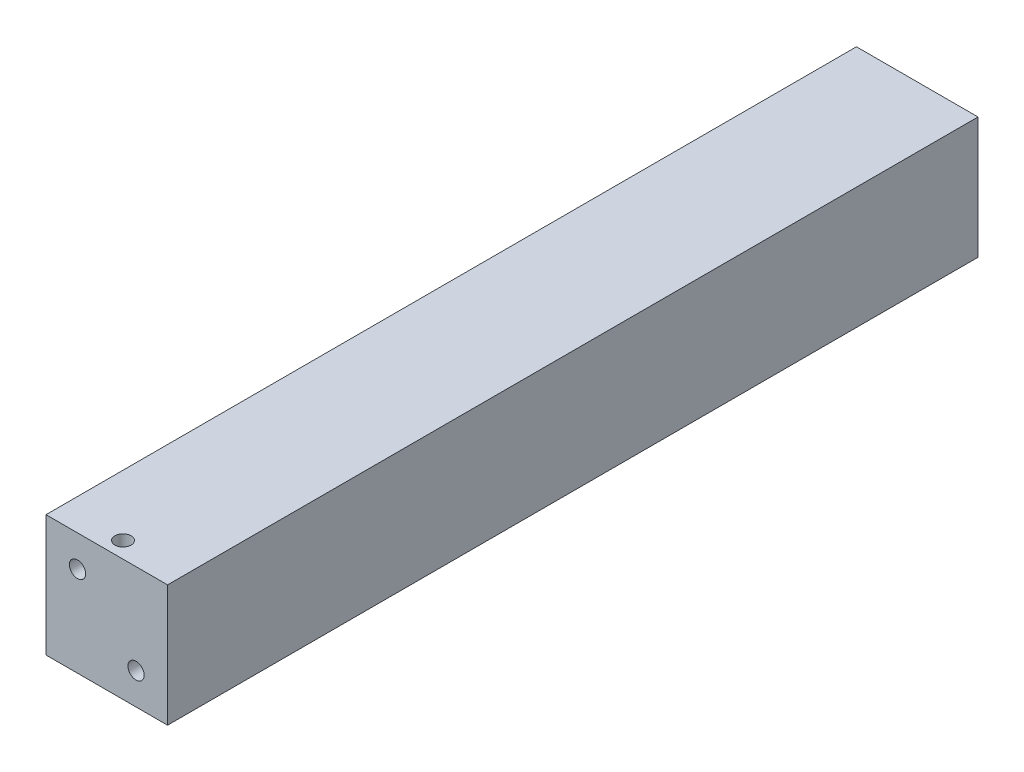
SolidWorks part; units mm, degrees
ref_plane "Alzado" through (0, 0, 0) normal (0, 0, 1) x (1, 0, 0)
ref_plane "Planta" through (0, 0, 0) normal (0, 1, 0) x (1, 0, 0)
ref_plane "Vista lateral" through (0, 0, 0) normal (1, 0, 0) x (0, 0, -1)
sketch "Croquis1" plane through (0, 0, 0) normal (0, 0, 1) x (1, 0, 0)
  line L1 (-15, -15) -> (15, -15)
  line L2 (-15, -15) -> (-15, 15)
  line L3 (-15, 15) -> (15, 15)
  line L4 (15, -15) -> (15, 15)
  line L5 (-15, -15) -> (15, 15) construction
  line L6 (-15, 15) -> (15, -15) construction
  point P0 (0, 0)
  dimension "D1" = 30
extrude "Saliente-Extruir1" add sketch "Croquis1" along normal blind 200
sketch "Croquis2" plane through (0, 0, 200) normal (0, 0, 1) x (1, 0, 0)
  line L0 (-15, 15) -> (15, -15) construction
  line L1 (-15, -15) -> (15, 15) construction
  circle A1 centre (-7.2218, 7.2218) radius 2
  circle A2 centre (7.2218, -7.2218) radius 2
  dimension "D1" = 11
extrude "Cortar-Extruir1" cut sketch "Croquis2" against normal blind 25
sketch "Croquis3" plane through (0, 15, 0) normal (0, 1, 0) x (1, 0, 0)
  line L0 (0, -200) -> (0, -196) construction
  line L1 (15, -200) -> (-15, -200) construction
  circle A0 centre (0, -196) radius 2
  dimension "D1" = 4
extrude "Cortar-Extruir2" cut sketch "Croquis3" against normal through all
sketch "Croquis4" plane through (0, 0, 0) normal (0, 0, -1) x (-1, 0, 0)
  circle A0 centre (0, 0) radius 2
extrude "Cortar-Extruir3" cut sketch "Croquis4" against normal blind 25
